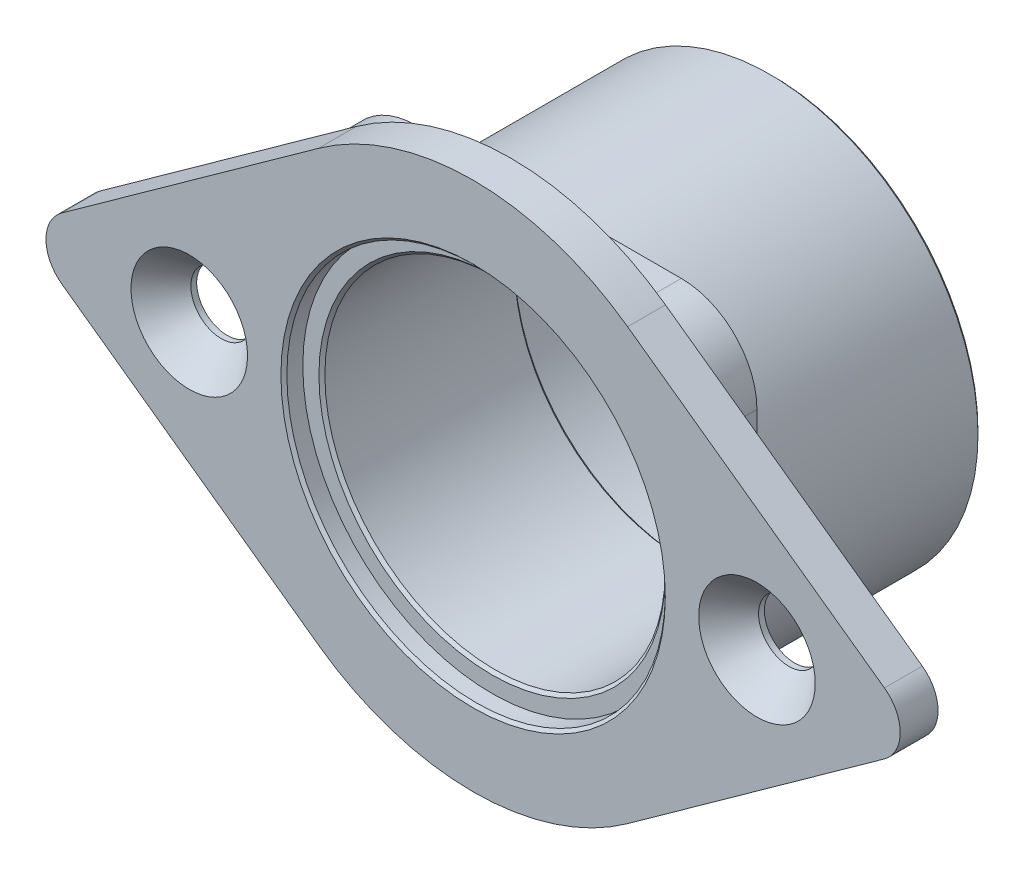
SolidWorks part; units mm, degrees
material "6061-T6 (SS)"
ref_plane "Front Plane" through (0, 0, 0) normal (0, 0, 1) x (1, 0, 0)
ref_plane "Top Plane" through (0, 0, 0) normal (0, 1, 0) x (1, 0, 0)
ref_plane "Right Plane" through (0, 0, 0) normal (1, 0, 0) x (0, 0, -1)
ref_plane "Plane1" through (0, 0, 1.5875) normal (0, 0, 1) x (1, 0, 0)
sketch "Sketch1" plane through (0, 0, 1.5875) normal (0, 0, 1) x (1, 0, 0)
  line L0 (-34.5092, -2.5788) -> (0, -27.3628)
  line L1 (0, -27.3628) -> (34.5092, -2.5788)
  line L2 (34.5092, 2.5788) -> (0, 27.3628)
  line L3 (0, 27.3628) -> (-34.5092, 2.5788)
  arc A0 (34.5092, -2.5788) -> (34.5092, 2.5788) centre (32.6571, 0) ccw
  arc A1 (-34.5092, 2.5788) -> (-34.5092, -2.5788) centre (-32.6571, 0) ccw
extrude "Boss-Extrude1" add sketch "Sketch1" against normal blind 3.175
sketch "Sketch2" plane through (0, 0, -1.5875) normal (0, 0, -1) x (-1, 0, 0)
  line L0 (11.1125, -17.4625) -> (-11.1125, -17.4625)
  line L1 (-17.4625, -11.1125) -> (-17.4625, 11.1125)
  line L2 (-11.1125, 17.4625) -> (11.1125, 17.4625)
  line L3 (17.4625, 11.1125) -> (17.4625, -11.1125)
  arc A0 (-11.1125, -17.4625) -> (-17.4625, -11.1125) centre (-11.1125, -11.1125) cw
  arc A1 (-17.4625, 11.1125) -> (-11.1125, 17.4625) centre (-11.1125, 11.1125) cw
  arc A2 (11.1125, 17.4625) -> (17.4625, 11.1125) centre (11.1125, 11.1125) cw
  arc A3 (17.4625, -11.1125) -> (11.1125, -17.4625) centre (11.1125, -11.1125) cw
extrude "Boss-Extrude2" add sketch "Sketch2" along normal blind 3.175
sketch "Sketch3" plane through (0, 0, 0) normal (0, 1, 0) x (1, 0, 0)
  line L0 (17.4625, 23.5585) -> (0, 23.5585)
  line L1 (0, 23.5585) -> (0, 4.7625)
  line L2 (0, 4.7625) -> (17.4625, 4.7625)
  line L3 (17.4625, 4.7625) -> (17.4625, 23.5585)
  line L4 (0, 23.5585) -> (0, 4.7625) construction
revolve "Revolve1" add sketch "Sketch3" angle 360 about L4
ref_plane "Plane2" through (0, 0, 0) normal (0, -1, 0) x (1, 0, 0)
sketch "Sketch4" plane through (0, 0, 0) normal (0, -1, 0) x (1, 0, 0)
  line L0 (15.875, 1.5875) -> (0, 1.5875)
  line L1 (0, 1.5875) -> (0, -23.5585)
  line L2 (0, -23.5585) -> (15.8687, -23.5585)
  line L3 (15.8687, -23.5585) -> (15.8687, -16.4147)
  line L4 (15.8687, -16.4147) -> (14.2748, -16.4147)
  line L5 (14.2748, -16.4147) -> (14.2748, 0)
  line L6 (14.2748, 0) -> (15.875, 0)
  line L7 (15.875, 0) -> (15.875, 1.5875)
  line L8 (0, 1.5875) -> (0, -23.5585) construction
revolve "Cut-Revolve1" cut sketch "Sketch4" angle 360 about L8
hole_wizard "Hole1" positions "Sketch6" profile "Sketch5" legacy end condition through all
sketch "Sketch6" plane through (0, 0, 1.5875) normal (0, 0, 1) x (1, 0, 0)
  point P0 (-23.8125, 0)
  point P1 (23.8125, 0)
sketch "Sketch5" plane through (-23.8125, 0, 1.5875) normal (1, 0, 0) x (0, -1, 0)
  line L0 (0, 0) -> (0, 25.146)
  line L1 (0, 25.146) -> (2.5527, 25.146)
  line L2 (2.5527, 25.146) -> (2.5527, 2.6882)
  line L3 (2.5527, 2.6882) -> (4.8895, 0)
  line L4 (4.8895, 0) -> (0, 0)
  line L5 (0, -6.4453) -> (0, 115.525) construction
  line L6 (-2.5527, 2.6882) -> (-4.8895, 0) construction
  dimension "Diameter" = 5.1054
  dimension "Depth" = 25.146
  dimension "C-Sink Angle" = 82
  dimension "C-Sink Diameter" = 9.779
chamfer "Chamfer1" distance 0.25 angle 45 5 edges at (-15.875, 0, 1.5875) (-15.8687, 0, -23.5585) (17.4625, 0, -23.5585) (-14.2748, 0, 0) (-14.2748, 0, -16.4147)
fillet "Fillet1" radius 22.225 2 edges at (0, -27.3628, 0) (0, 27.3628, 0)
